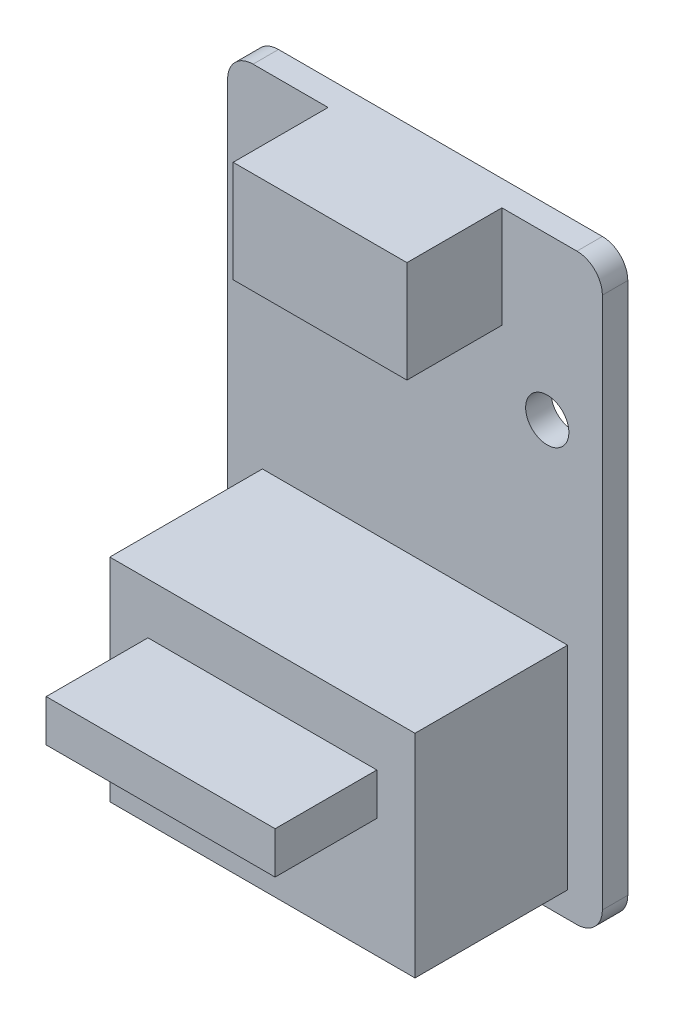
SolidWorks part; units mm, degrees
ref_plane "前基準面" through (0, 0, 0) normal (0, 0, 1) x (1, 0, 0)
ref_plane "上基準面" through (0, 0, 0) normal (0, 1, 0) x (1, 0, 0)
ref_plane "右基準面" through (0, 0, 0) normal (1, 0, 0) x (0, 0, -1)
sketch "草圖1" plane through (0, 0, 0) normal (0, 0, 1) x (1, 0, 0)
  line L0 (16.5192, -95.372) -> (23.0192, -95.372) construction
  line L1 (-6.7606, -60.972) -> (12.3394, -60.972)
  line L2 (-8.2606, -62.472) -> (-8.2606, -93.872)
  line L3 (-6.7606, -95.372) -> (12.3394, -95.372)
  line L4 (13.8394, -62.472) -> (13.8394, -93.872)
  arc A0 (12.3394, -95.372) -> (13.8394, -93.872) centre (12.3394, -93.872) ccw
  arc A1 (-8.2606, -93.872) -> (-6.7606, -95.372) centre (-6.7606, -93.872) ccw
  arc A2 (-6.7606, -60.972) -> (-8.2606, -62.472) centre (-6.7606, -62.472) ccw
  arc A3 (12.3394, -60.972) -> (13.8394, -62.472) centre (12.3394, -62.472) cw
  point P8 (-8.2606, -95.372)
  point P11 (-8.2606, -60.972)
  point P14 (13.8394, -60.972)
  dimension "D3" = 1.5
  dimension "D1" = 22.1
  dimension "D2" = 34.4
  dimension "D4" = 0
extrude "填料-伸長1" add sketch "草圖1" along normal blind 1.5
sketch "草圖2" plane through (0, 0, 1.5) normal (0, 0, 1) x (1, 0, 0)
  line L0 (-6.7606, -95.372) -> (12.3394, -95.372) construction
  line L1 (-6.2106, -81.372) -> (11.7894, -81.372)
  line L2 (-6.2106, -81.372) -> (-6.2106, -93.872)
  line L3 (-6.2106, -93.872) -> (11.7894, -93.872)
  line L4 (11.7894, -81.372) -> (11.7894, -93.872)
  point P6 (2.7894, -95.372)
  point P7 (2.7894, -93.872)
  dimension "D1" = 18
  dimension "D2" = 12.5
  dimension "D3" = 1.5
extrude "填料-伸長2" add sketch "草圖2" along normal blind 9
sketch "草圖3" plane through (0, 0, 10.5) normal (0, 0, 1) x (1, 0, 0)
  line L0 (-6.2106, -93.872) -> (11.7894, -93.872) construction
  line L1 (-3.9606, -84.372) -> (9.5394, -84.372)
  line L2 (-3.9606, -84.372) -> (-3.9606, -86.8442)
  line L3 (-3.9606, -86.8442) -> (9.5394, -86.8442)
  line L4 (9.5394, -84.372) -> (9.5394, -86.8442)
  line L5 (11.7894, -81.372) -> (-6.2106, -81.372) construction
  point P4 (2.7894, -86.8442)
  point P7 (2.7894, -93.872)
  dimension "D1" = 3
extrude "填料-伸長3" add sketch "草圖3" along normal blind 6
sketch "草圖4" plane through (0, 0, 1.5) normal (0, 0, 1) x (1, 0, 0)
  line L0 (12.3394, -60.972) -> (-6.7606, -60.972) construction
  line L1 (-2.3356, -60.972) -> (7.9144, -60.972)
  line L2 (-2.3356, -60.972) -> (-2.3356, -66.972)
  line L3 (-2.3356, -66.972) -> (7.9144, -66.972)
  line L4 (7.9144, -60.972) -> (7.9144, -66.972)
  point P6 (2.7894, -60.972)
  point P7 (2.7894, -60.972)
  dimension "D1" = 10.25
  dimension "D2" = 6
extrude "填料-伸長4" add sketch "草圖4" along normal blind 5.6
hole_wizard "M2.5 螺旋的螺孔鑽1" positions "草圖5" profile "草圖6" hole size "M2.5x0.45" standard "Ansi Metric" end condition through all
sketch "草圖5" plane through (0, 0, 1.5) normal (0, 0, 1) x (1, 0, 0)
  line L0 (-8.2606, -62.472) -> (-8.2606, -93.872) construction
  line L1 (13.8394, -93.872) -> (13.8394, -62.472) construction
  line L2 (12.3394, -60.972) -> (7.9144, -60.972) construction
  line L3 (-2.3356, -60.972) -> (-6.7606, -60.972) construction
  point P0 (-5.0106, -70.472)
  point P2 (10.5894, -70.472)
  dimension "D1" = 3.25
  dimension "D2" = 3.25
  dimension "D3" = 9.5
  dimension "D4" = 9.5
sketch "草圖6" plane through (-5.0106, -70.472, 1.5) normal (1, 0, 0) x (0, -1, 0)
  line L0 (0, 0) -> (0, 1.5)
  line L1 (0, 1.5) -> (1.275, 1.5)
  line L2 (1.275, 1.5) -> (1.275, 0)
  line L5 (1.275, 0) -> (0, 0)
  line L11 (0, -6.35) -> (0, 107.95) construction
  dimension "貫穿孔直徑" = 2.55
  dimension "貫穿孔深度" = 1.5
